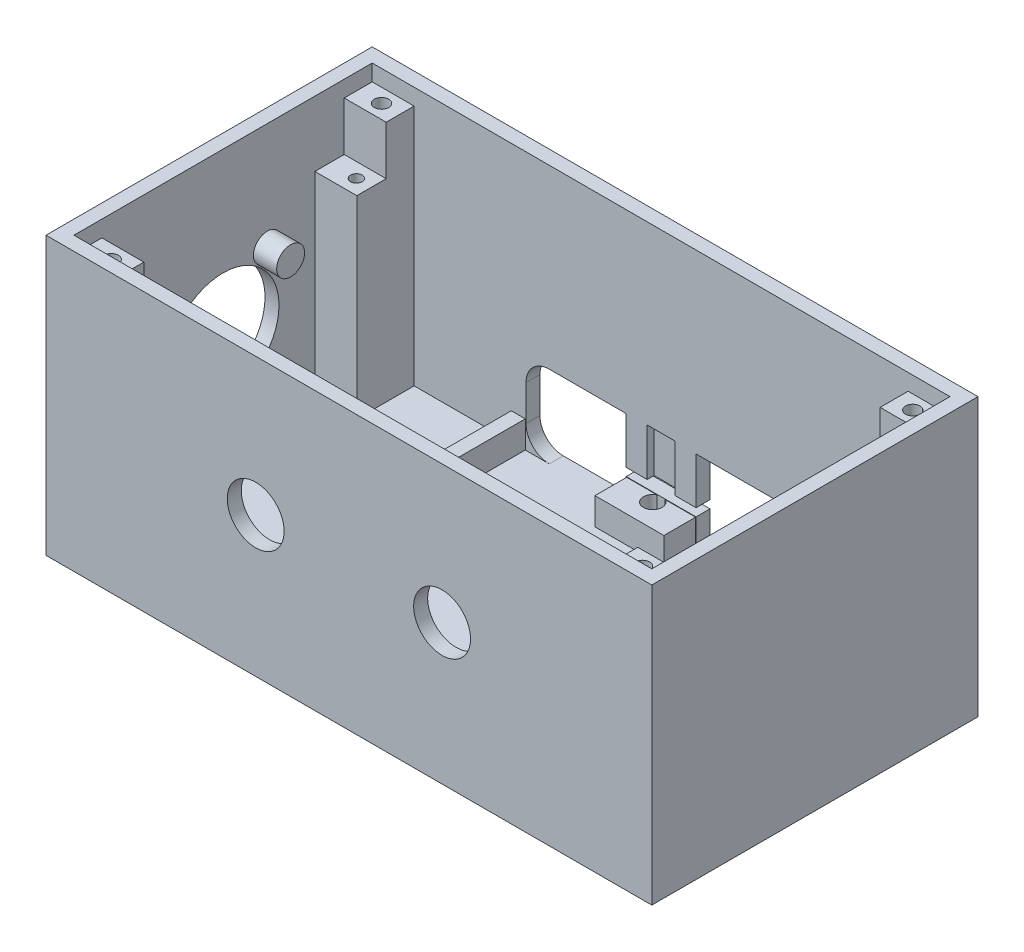
SolidWorks part; units mm, degrees
ref_plane "Ebene vorne" through (0, 0, 0) normal (0, 0, 1) x (1, 0, 0)
ref_plane "Ebene oben" through (0, 0, 0) normal (0, 1, 0) x (1, 0, 0)
ref_plane "Ebene rechts" through (0, 0, 0) normal (1, 0, 0) x (0, 0, -1)
sketch "Sketch1" plane through (0, 0, 0) normal (0, 1, 0) x (1, 0, 0)
  line L1 (-65, -35) -> (65, -35)
  line L2 (-65, -35) -> (-65, 35)
  line L3 (-65, 35) -> (65, 35)
  line L4 (65, -35) -> (65, 35)
  line L5 (-65, -35) -> (65, 35) construction
  line L6 (-65, 35) -> (65, -35) construction
  line L11 (-60, -14.8618) -> (60, -14.8618) construction
  line L12 (-60, -14.8618) -> (-60, -29.7) construction
  line L13 (-60, -29.7) -> (60, -29.7) construction
  line L14 (60, -14.8618) -> (60, -29.7) construction
  line L15 (-63, 8.4731) -> (-19.5, 8.4731) construction
  line L16 (-63, 8.4731) -> (-63, -9.3269) construction
  line L17 (-63, -9.3269) -> (-19.5, -9.3269) construction
  line L18 (-19.5, 8.4731) -> (-19.5, -9.3269) construction
  line L19 (-29, 35) -> (29, 35) construction
  line L20 (-29, 35) -> (-29, 12.5) construction
  line L21 (-29, 12.5) -> (29, 12.5) construction
  line L22 (29, 35) -> (29, 12.5) construction
  point P0 (0, 0)
  dimension "D1" = 130
  dimension "D2" = 70
  dimension "D3" = 120
  dimension "D4" = 5
  dimension "D5" = 5.3
  dimension "D6" = 43.5
  dimension "D7" = 17.8
  dimension "D8" = 2
  dimension "D9" = 22.5
  dimension "D10" = 58
  dimension "D11" = 29
extrude "Extrude1" add sketch "Sketch1" along normal blind 4 contours L2 L1 L4 L3
sketch "Sketch2" plane through (0, 4, 0) normal (0, 1, 0) x (1, 0, 0)
  line L0 (65, -35) -> (65, 35) construction
  line L1 (-65, 35) -> (65, 35)
  line L2 (-65, 35) -> (-65, 32)
  line L3 (-65, 32) -> (65, 32)
  line L4 (65, 35) -> (65, 32)
  line L5 (-65, -35) -> (65, -35) construction
  line L6 (-65, 35) -> (-62, 35)
  line L7 (-65, 35) -> (-65, -35)
  line L8 (-65, -35) -> (-62, -35)
  line L9 (-62, 35) -> (-62, -35)
  line L11 (65, -35) -> (62, -35)
  line L12 (65, -35) -> (65, 35)
  line L13 (65, 35) -> (62, 35)
  line L14 (62, -35) -> (62, 35)
  line L15 (-65, -35) -> (65, -35)
  line L16 (-65, -35) -> (-65, -32)
  line L17 (-65, -32) -> (65, -32)
  line L18 (65, -35) -> (65, -32)
  line M4 (65, 35) -> (-65, 35)
  line M5 (-65, 35) -> (-65, -35)
  line M6 (-65, -35) -> (65, -35)
  line M7 (65, -35) -> (65, 35)
  dimension "D1" = 3
  dimension "D2" = 3
  dimension "D3" = 3
  dimension "D4" = 3
  dimension "D5" = 130
extrude "Extrude2" add sketch "Sketch2" along normal blind 55.5 contours L9 L3 M5 M6 | L3 L14 L1 L9 | L14 L3 M6 M7 | L9 L1 L3 M5 | L14 L3 M7 M4 | L17 L7 L9 M6 | L17 L9 L14 M6 | L17 L14 M6 M7
sketch "Sketch3" plane through (0, 0, -35) normal (0, 0, -1) x (-1, 0, 0)
  line L0 (65, 0) -> (-65, 0) construction
  line L1 (-24, 21.6) -> (-7.5, 21.6)
  line L2 (-29, 16.6) -> (-29, 9)
  line L3 (-24, 4) -> (-7.5, 4)
  line L4 (-7.5, 21.6) -> (-7.5, 4)
  line L5 (7.5, 21.6) -> (24, 21.6)
  line L6 (7.5, 21.6) -> (7.5, 4)
  line L7 (7.5, 4) -> (24, 4)
  line L8 (29, 16.6) -> (29, 9)
  line L10 (-7.5, 11.6) -> (7.5, 11.6)
  line L11 (-7.5, 11.6) -> (-7.5, 9.9)
  line L12 (-7.5, 9.9) -> (7.5, 9.9)
  line L13 (7.5, 11.6) -> (7.5, 9.9)
  arc A0 (24, 21.6) -> (29, 16.6) centre (24, 16.6) cw
  arc A1 (24, 4) -> (29, 9) centre (24, 9) ccw
  arc A2 (-29, 9) -> (-24, 4) centre (-24, 9) ccw
  arc A3 (-24, 21.6) -> (-29, 16.6) centre (-24, 16.6) ccw
  dimension "D4" = 17.6
  dimension "D5" = 5
  dimension "D3" = 7.5
  dimension "D6" = 15
  dimension "D7" = 4
  dimension "D8" = 10
  dimension "D9" = 1.7
extrude "Extrude3" cut sketch "Sketch3" against normal blind 4.8 contours L1 A3 L2 A2 L3 L4 | L7 A1 L8 A0 L5 L6 | L4 L12 L6 L10
sketch "Sketch4" plane through (0, 4, 0) normal (0, 1, 0) x (1, 0, 0)
  line L0 (-62, 32) -> (62, 32) construction
  line L1 (-7.4, 32) -> (7.4, 32)
  line L2 (-7.4, 32) -> (-7.4, 25.2)
  line L3 (-7.4, 25.2) -> (7.4, 25.2)
  line L4 (7.4, 32) -> (7.4, 25.2)
  line L5 (-62, 32) -> (-24, 32) construction
  line L6 (-32.15, 32) -> (-29.15, 32)
  line L7 (-32.15, 32) -> (-32.15, 17)
  line L8 (-32.15, 17) -> (-29.15, 17)
  line L9 (-29.15, 32) -> (-29.15, 17)
  line L10 (24, 32) -> (62, 32) construction
  line L11 (29.15, 32) -> (32.15, 32)
  line L12 (29.15, 32) -> (29.15, 17)
  line L13 (29.15, 17) -> (32.15, 17)
  line L14 (32.15, 32) -> (32.15, 17)
  circle A0 centre (0, 30.2) radius 2
  line M6 (-24, 32) -> (-62, 32)
  line M10 (62, 32) -> (24, 32)
  line M14 (7.5, 32) -> (-7.5, 32)
  dimension "D4" = 4
  dimension "D1" = 14.8
  dimension "D2" = 7.4
  dimension "D3" = 6.8
  dimension "D5" = 5
  dimension "D6" = 3
  dimension "D7" = 3
  dimension "D8" = 58.3
  dimension "D9" = 29.15
  dimension "D10" = 15
extrude "Extrude5" add sketch "Sketch4" along normal blind 5.8 contours A0 L2 L3 L4 M14 | L9 L7 L8 M6 | L14 L12 L13 M10
sketch "Sketch5" plane through (0, 0, -32) normal (0, 0, 1) x (1, 0, 0)
  line L0 (7.5, 11.6) -> (-7.5, 11.6) construction
  line L1 (-3, 11.6) -> (3, 11.6)
  line L2 (-3, 11.6) -> (-3, 21.7393)
  line L3 (-3, 21.7393) -> (3, 21.7393)
  line L4 (3, 11.6) -> (3, 21.7393)
  line L5 (7.5, 21.6) -> (7.5, 11.6) construction
  dimension "D1" = 6
  dimension "D2" = 4.5
extrude "Extrude6" cut sketch "Sketch5" against normal blind 1.5
sketch "Sketch22" plane through (-65, 0, 0) normal (-1, 0, 0) x (0, 0, 1)
  line L0 (-35, 59.5) -> (-35, 0) construction
  line L1 (35, 59.5) -> (35, 0) construction
  line L2 (-35, 59.5) -> (35, 59.5) construction
  line L3 (35, 0) -> (-35, 0) construction
  circle A0 centre (-9.5, 36.5) radius 3
  circle A1 centre (9.5, 12.5) radius 3
  dimension "D1" = 6
  dimension "D2" = 6
  dimension "D3" = 25.5
  dimension "D4" = 25.5
  dimension "D5" = 23
  dimension "D6" = 12.5
extrude "Extrude26" add sketch "Sketch22" against normal blind 8
sketch "Sketch10" plane through (-65, 0, 0) normal (-1, 0, 0) x (0, 0, 1)
  line L0 (-35, 59.5) -> (35, 59.5) construction
  line L1 (-13, 40) -> (13, 40) construction
  line L2 (-13, 40) -> (-13, 9) construction
  line L3 (-13, 9) -> (13, 9) construction
  line L4 (13, 40) -> (13, 9) construction
  circle A0 centre (0, 24.5) radius 12
  circle A1 centre (-9.5, 36.5) radius 1.5
  circle A2 centre (9.5, 12.5) radius 1.5
  dimension "D1" = 24
  dimension "D8" = 3
  dimension "D11" = 3
  dimension "D2" = 26
  dimension "D3" = 31
  dimension "D4" = 13
  dimension "D5" = 15.5
  dimension "D6" = 35
  dimension "D7" = 35
  dimension "D9" = 3.5
  dimension "D10" = 3.5
  dimension "D12" = 3.5
  dimension "D13" = 3.5
extrude "Extrude11" cut sketch "Sketch10" against normal blind 6 contours A0 | A1 | A2
sketch "Sketch12" plane through (0, 59.5, 0) normal (0, 1, 0) x (1, 0, 0)
  line L23 (-62, -32) -> (-53, -32)
  line L24 (-62, -32) -> (-62, -26)
  line L25 (-62, -26) -> (-53, -26)
  line L26 (-53, -32) -> (-53, -26)
  line L28 (62, -32) -> (53, -32)
  line L29 (62, -32) -> (62, -26)
  line L30 (62, -26) -> (53, -26)
  line L31 (53, -32) -> (53, -26)
  dimension "D3" = 9
  dimension "D4" = 9
  dimension "D2" = 6
  dimension "D1" = 6
extrude "Extrude13" add sketch "Sketch12" against normal blind 52 from offset 3.5 offset against normal yes
sketch "Sketch13" plane through (0, 59.5, 0) normal (0, 1, 0) x (1, 0, 0)
  line L1 (-62, 32) -> (-53, 32)
  line L2 (-62, 32) -> (-62, 26)
  line L3 (-62, 26) -> (-53, 26)
  line L4 (-53, 32) -> (-53, 26)
  line L5 (62, 32) -> (53, 32)
  line L6 (62, 32) -> (62, 26)
  line L7 (62, 26) -> (53, 26)
  line L8 (53, 32) -> (53, 26)
  dimension "D2" = 9
  dimension "D4" = 9
  dimension "D1" = 6
  dimension "D3" = 6
extrude "Extrude14" add sketch "Sketch13" against normal blind 52 from offset 3.5 offset against normal yes
sketch "Sketch14" plane through (0, 59.5, 0) normal (0, 1, 0) x (1, 0, 0)
  line L5 (65, 35) -> (-65, 35) construction
  line L6 (65, -35) -> (65, 35) construction
  line L7 (-65, 35) -> (-65, -35) construction
  circle A1 centre (-57, 29) radius 1.55
  circle A2 centre (57, 29) radius 1.55
  dimension "D1" = 3.1
  dimension "D4" = 3.1
  dimension "D2" = 6
  dimension "D3" = 8
  dimension "D5" = 6
  dimension "D6" = 8
extrude "Extrude15" cut sketch "Sketch14" against normal blind 8
sketch "Sketch20" plane through (0, 59.5, 0) normal (0, 1, 0) x (1, 0, 0)
  line L0 (-65, 35) -> (-65, -35) construction
  line L1 (-65, -35) -> (65, -35) construction
  line L2 (65, -35) -> (65, 35) construction
  circle A0 centre (-57, -29) radius 1.55
  circle A1 centre (57, -29) radius 1.55
  dimension "D1" = 3.1
  dimension "D4" = 3.1
  dimension "D2" = 8
  dimension "D3" = 6
  dimension "D5" = 8
  dimension "D6" = 6
extrude "Extrude22" cut sketch "Sketch20" against normal blind 8
sketch "Sketch23" plane through (0, 4, 0) normal (0, 1, 0) x (1, 0, 0)
  line L1 (-60, -25.4) -> (60, -25.4) construction
  line L2 (-60, -25.4) -> (-60, 25.4) construction
  line L3 (-60, 25.4) -> (60, 25.4) construction
  line L4 (60, -25.4) -> (60, 25.4) construction
  line L5 (-60, -25.4) -> (60, 25.4) construction
  line L6 (-60, 25.4) -> (60, -25.4) construction
  line L7 (-62, 26) -> (-53, 26)
  line L8 (-62, 26) -> (-62, 19.7)
  line L9 (-62, 19.7) -> (-53, 19.7)
  line L10 (-53, 26) -> (-53, 19.7)
  line L11 (-62, -26) -> (-53, -26)
  line L12 (-62, -26) -> (-62, -19.7)
  line L13 (-62, -19.7) -> (-53, -19.7)
  line L14 (-53, -26) -> (-53, -19.7)
  line L15 (62, -26) -> (53, -26)
  line L16 (62, -26) -> (62, -19.7)
  line L17 (62, -19.7) -> (53, -19.7)
  line L18 (53, -26) -> (53, -19.7)
  line L19 (62, 26) -> (53, 26)
  line L20 (62, 26) -> (62, 19.7)
  line L21 (62, 19.7) -> (53, 19.7)
  line L22 (53, 26) -> (53, 19.7)
  circle A0 centre (-57.46, 22.86) radius 1.5 construction
  circle A1 centre (-57.46, -22.86) radius 1.5 construction
  circle A2 centre (57.46, -22.86) radius 1.5 construction
  circle A3 centre (57.46, 22.86) radius 1.5 construction
  point P0 (0, 0)
  dimension "D4" = 3
  dimension "D7" = 9
  dimension "D9" = 3
  dimension "D12" = 3
  dimension "D15" = 3
  dimension "D1" = 120
  dimension "D2" = 50.8
  dimension "D3" = 0
  dimension "D5" = 2.54
  dimension "D6" = 2.54
  dimension "D8" = 6.3
  dimension "D10" = 2.54
  dimension "D11" = 2.54
  dimension "D13" = 2.54
  dimension "D14" = 2.54
  dimension "D16" = 2.54
  dimension "D17" = 2.54
  dimension "D18" = 6.3
  dimension "D19" = 9
  dimension "D20" = 6.3
  dimension "D21" = 9
  dimension "D22" = 6.3
  dimension "D23" = 9
extrude "Extrude27" add sketch "Sketch23" along normal blind 41.5
sketch "Sketch24" plane through (0, 0, 35) normal (0, 0, 1) x (1, 0, 0)
  line L1 (-65, 0) -> (65, 0) construction
  circle A0 centre (-20, 30) radius 6.1
  circle A1 centre (20, 30) radius 6.1
  dimension "D1" = 12.2
  dimension "D2" = 12.2
  dimension "D3" = 30
  dimension "D4" = 30
  dimension "D5" = 40
  dimension "D6" = 20
extrude "Extrude28" cut sketch "Sketch24" against normal blind 5
sketch "Sketch25" plane through (0, 45.5, 0) normal (0, 1, 0) x (1, 0, 0)
  circle A0 centre (-56.25, 22.86) radius 1.25
  circle A1 centre (56.25, 22.86) radius 1.25
  circle A2 centre (-56.25, -22.86) radius 1.25
  circle A3 centre (56.25, -22.86) radius 1.25
  dimension "D1" = 2.5
  dimension "D2" = 2.5
  dimension "D3" = 2.5
  dimension "D4" = 2.5
  dimension "D5" = 45.72
  dimension "D6" = 22.86
  dimension "D7" = 112.5
  dimension "D8" = 112.5
  dimension "D9" = 56.25
  dimension "D10" = 56.25
  dimension "D11" = 45.72
  dimension "D12" = 22.86
extrude "Extrude29" cut sketch "Sketch25" against normal blind 8
